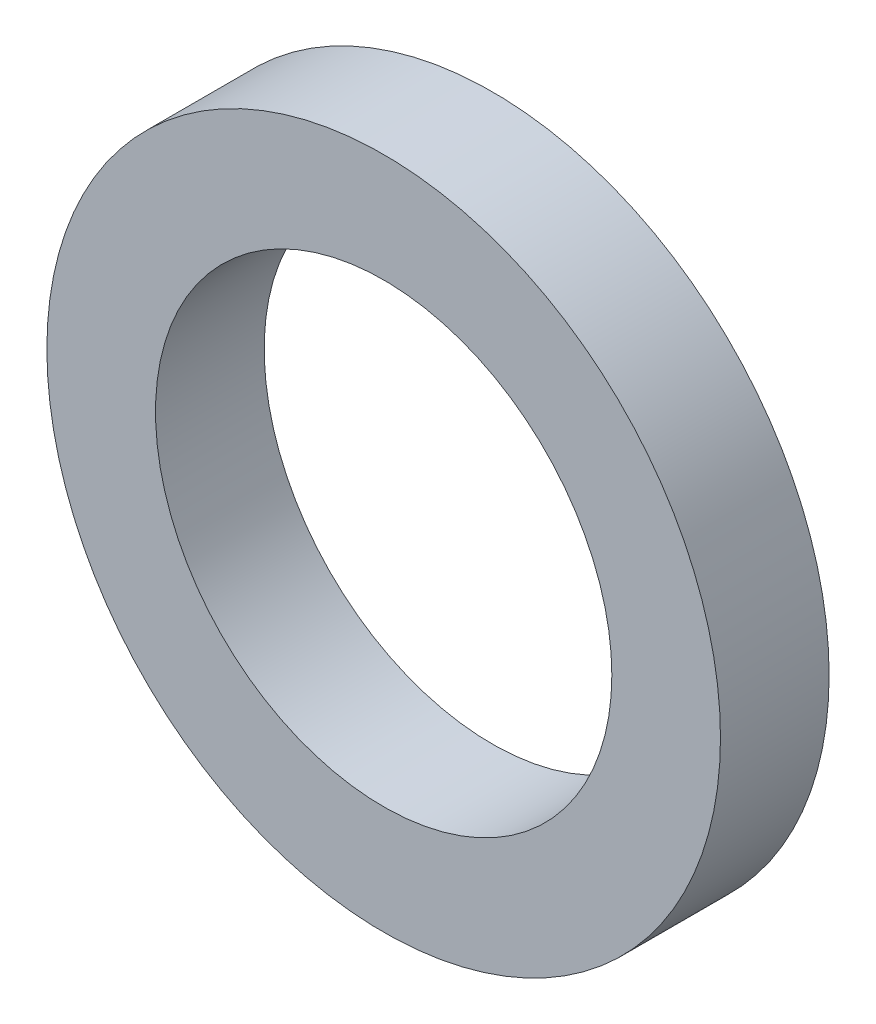
SolidWorks part; units mm, degrees
ref_plane "Front Plane" through (0, 0, 0) normal (0, 0, 1) x (1, 0, 0)
ref_plane "Top Plane" through (0, 0, 0) normal (0, 1, 0) x (1, 0, 0)
ref_plane "Right Plane" through (0, 0, 0) normal (1, 0, 0) x (0, 0, -1)
sketch "Sketch2" plane through (0, 0, 0) normal (0, 0, 1) x (1, 0, 0)
  circle A0 centre (0, 0) radius 3.1
  dimension "D1" = 6.2
extrude "Boss-Extrude1" add sketch "Sketch2" along normal blind 1
sketch "Sketch3" plane through (0, 0, 1) normal (0, 0, 1) x (1, 0, 0)
  circle A0 centre (0, 0) radius 2.1
  dimension "D1" = 4.2
extrude "Cut-Extrude1" cut sketch "Sketch3" against normal through all
